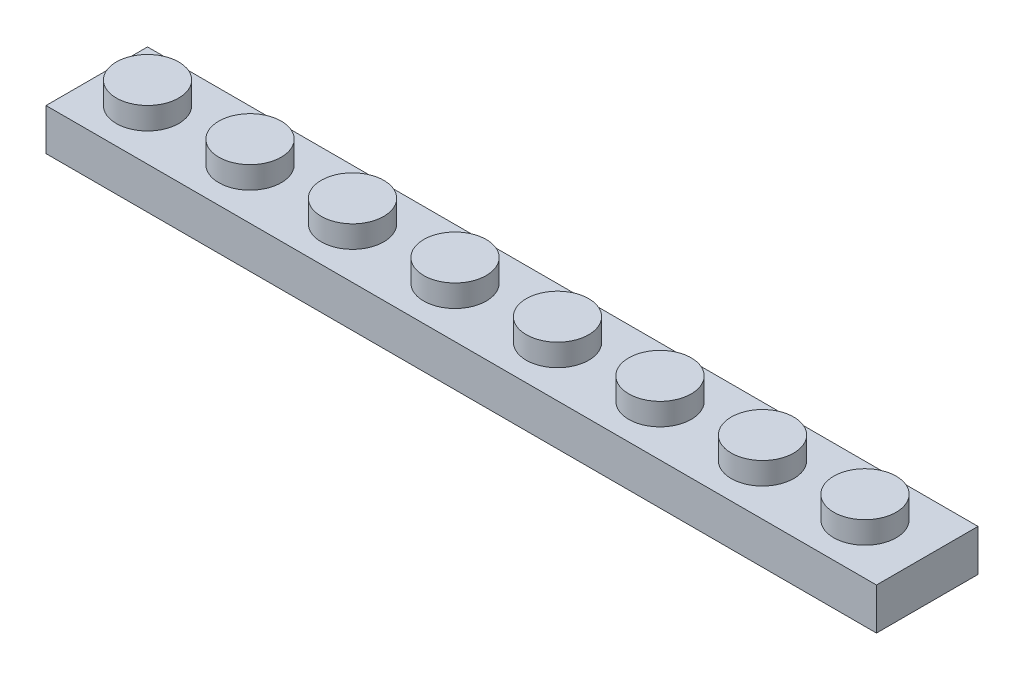
SolidWorks part; units mm, degrees
ref_plane "Спереди" through (0, 0, 0) normal (0, 0, 1) x (1, 0, 0)
ref_plane "Сверху" through (0, 0, 0) normal (0, 1, 0) x (1, 0, 0)
ref_plane "Справа" through (0, 0, 0) normal (1, 0, 0) x (0, 0, -1)
sketch "Эскиз1" plane through (0, 0, 0) normal (0, 1, 0) x (1, 0, 0)
  line L1 (31.9, -3.9) -> (-31.9, -3.9)
  line L2 (31.9, -3.9) -> (31.9, 3.9)
  line L3 (31.9, 3.9) -> (-31.9, 3.9)
  line L4 (-31.9, -3.9) -> (-31.9, 3.9)
  line L5 (31.9, -3.9) -> (-31.9, 3.9) construction
  line L6 (31.9, 3.9) -> (-31.9, -3.9) construction
  point P0 (0, 0)
  dimension "D1" = 63.8
  dimension "D2" = 7.8
extrude "Бобышка-Вытянуть1" add sketch "Эскиз1" along normal blind 3.2
sketch "Эскиз2" plane through (0, 3.2, 0) normal (0, 1, 0) x (1, 0, 0)
  line L0 (-31.9, 3.9) -> (-31.9, -3.9) construction
  line L1 (-31.9, -3.9) -> (31.9, -3.9) construction
  circle A0 centre (-28, 0) radius 2.4
  circle A1 centre (-20.126, 0) radius 2.4
  circle A2 centre (-12.252, 0) radius 2.4
  circle A3 centre (-4.378, 0) radius 2.4
  circle A4 centre (3.496, 0) radius 2.4
  circle A5 centre (11.37, 0) radius 2.4
  circle A6 centre (19.244, 0) radius 2.4
  circle A7 centre (27.118, 0) radius 2.4
  dimension "D1" = 3.9
  dimension "D2" = 3.9
  dimension "D3" = 8
extrude "Бобышка-Вытянуть2" add sketch "Эскиз2" along normal blind 1.7
sketch "Эскиз3" plane through (0, 0, 0) normal (0, -1, 0) x (1, 0, 0)
  line L0 (-31.9, -3.9) -> (-31.9, 3.9) construction
  line L1 (31.9, -3.9) -> (-31.9, -3.9) construction
  circle A0 centre (-28, 0) radius 2.5
  circle A1 centre (-20.126, 0) radius 2.5
  circle A2 centre (-12.252, 0) radius 2.5
  circle A3 centre (-4.378, 0) radius 2.5
  circle A4 centre (3.496, 0) radius 2.5
  circle A5 centre (11.37, 0) radius 2.5
  circle A6 centre (19.244, 0) radius 2.5
  circle A7 centre (27.118, 0) radius 2.5
  dimension "D1" = 3.9
  dimension "D2" = 3.9
  dimension "D3" = 8
extrude "Вырез-Вытянуть1" cut sketch "Эскиз3" against normal blind 1.8
